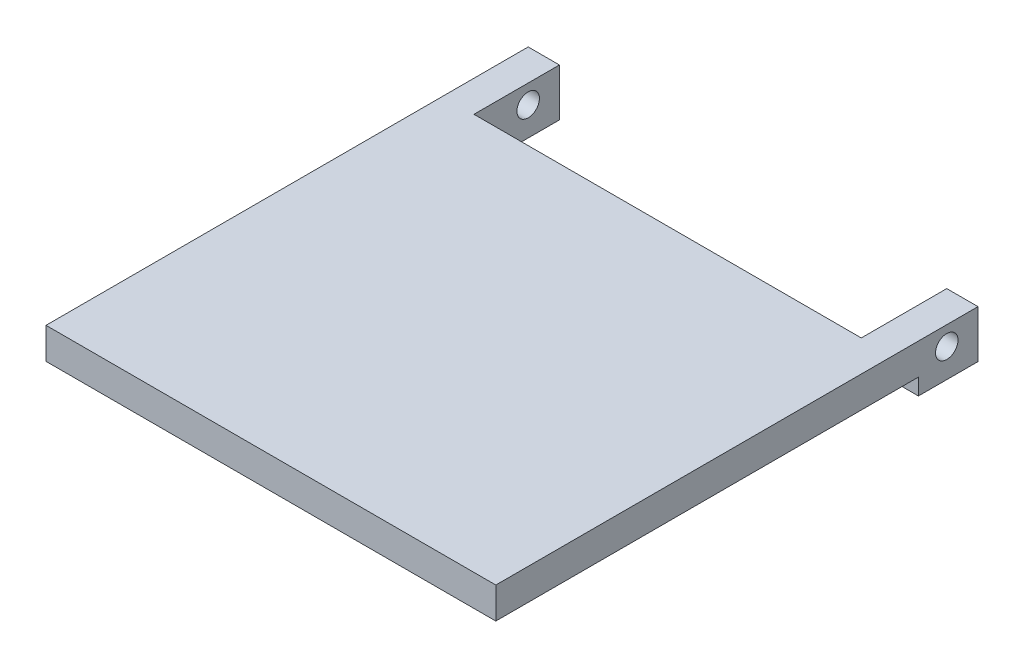
SolidWorks part; units mm, degrees
ref_plane "Front" through (0, 0, 0) normal (0, 0, 1) x (1, 0, 0)
ref_plane "Top" through (0, 0, 0) normal (0, 1, 0) x (1, 0, 0)
ref_plane "Right" through (0, 0, 0) normal (1, 0, 0) x (0, 0, -1)
sketch "Sketch1" plane through (0, 0, 0) normal (0, 1, 0) x (1, 0, 0)
  line L1 (0, 0) -> (72, 0)
  line L2 (0, 0) -> (0, -47)
  line L3 (0, -47) -> (72, -47)
  line L4 (72, 0) -> (72, -47)
  line L5 (0, 0) -> (5, 0)
  line L6 (0, 0) -> (0, 13)
  line L7 (0, 13) -> (5, 13)
  line L8 (5, 0) -> (5, 13)
  line L9 (72, 0) -> (67, 0)
  line L10 (72, 0) -> (72, 13.6822)
  line L11 (72, 13.6822) -> (67, 13.6822)
  line L12 (67, 0) -> (67, 13.6822)
  dimension "D1" = 5
  dimension "D2" = 5
  dimension "D3" = 72
  dimension "D4" = 60
  dimension "D5" = 13
extrude "Boss-Extrude1" add sketch "Sketch1" along normal blind 5 contours L4 L1 L2 L3 | L12 L1 L10 L11 | L6 L7 L8 L5
sketch "Sketch3" plane through (72, 0, 0) normal (1, 0, 0) x (0, 0, -1)
  line L0 (-0.2787, 6.9754) -> (-0.3353, -0.3244) construction
  line L1 (13.6822, 5) -> (-0.3532, 5)
  line L2 (13.6822, 5) -> (13.6822, -2.6238)
  line L3 (13.6822, -2.6238) -> (-0.3532, -2.6238)
  line L4 (-0.3532, 5) -> (-0.3532, -2.6238)
extrude "Boss-Extrude3" add sketch "Sketch3" against normal blind 5
sketch "Sketch5" plane through (0, 0, 0) normal (-1, 0, 0) x (0, 0, 1)
  line L1 (-13.6822, 5) -> (0.3532, 5)
  line L2 (-13.6822, 5) -> (-13.6822, -2.6238)
  line L3 (-13.6822, -2.6238) -> (0.3532, -2.6238)
  line L4 (0.3532, 5) -> (0.3532, -2.6238)
extrude "Boss-Extrude4" add sketch "Sketch5" against normal blind 5
sketch "Sketch4" plane through (72, 0, 0) normal (1, 0, 0) x (0, 0, -1)
  circle A0 centre (4.1826, 1.9724) radius 1.8
extrude "Cut-Extrude1" cut sketch "Sketch4" against normal blind 95
sketch "Sketch6" plane through (0, 0, 47) normal (0, 0, 1) x (1, 0, 0)
  line L1 (0, 0) -> (72, 0)
  line L2 (0, 0) -> (0, 5)
  line L3 (0, 5) -> (72, 5)
  line L4 (72, 0) -> (72, 5)
extrude "Boss-Extrude5" add sketch "Sketch6" along normal blind 21
sketch "Sketch8" plane through (0, 0, -13.6822) normal (0, 0, -1) x (-1, 0, 0)
  line L1 (16.5962, 20.9729) -> (-97.8892, 20.9729)
  line L2 (16.5962, 20.9729) -> (16.5962, -24.1683)
  line L3 (16.5962, -24.1683) -> (-97.8892, -24.1683)
  line L4 (-97.8892, 20.9729) -> (-97.8892, -24.1683)
extrude "Cut-Extrude2" cut sketch "Sketch8" against normal blind 4.5
sketch "Sketch9" plane through (0, 0, 0) normal (0, 0, -1) x (-1, 0, 0)
  line L1 (-5, 5) -> (-67, 5)
  line L2 (-5, 5) -> (-5, 0)
  line L3 (-5, 0) -> (-67, 0)
  line L4 (-67, 5) -> (-67, 0)
extrude "Cut-Extrude3" cut sketch "Sketch9" against normal blind 4.5
